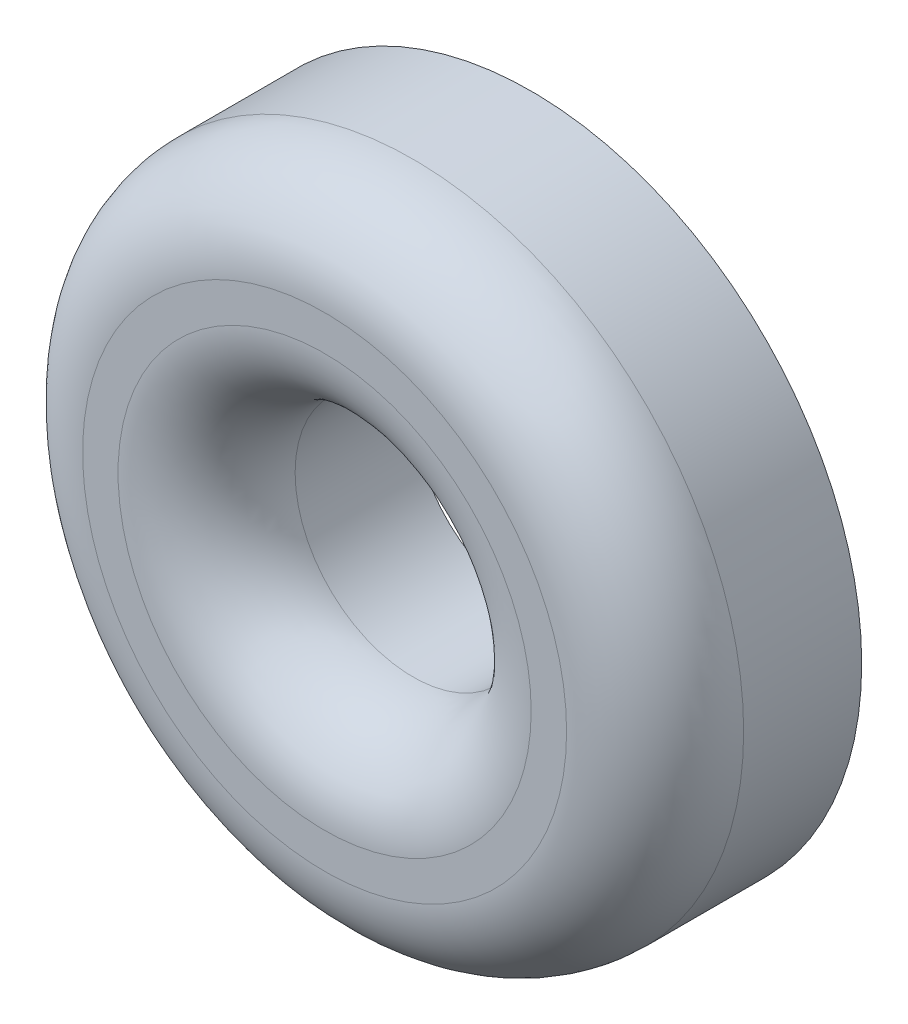
SolidWorks part; units mm, degrees
ref_plane "Front Plane" through (0, 0, 0) normal (0, 0, 1) x (1, 0, 0)
ref_plane "Top Plane" through (0, 0, 0) normal (0, 1, 0) x (1, 0, 0)
ref_plane "Right Plane" through (0, 0, 0) normal (1, 0, 0) x (0, 0, -1)
sketch "Sketch1" plane through (0, 0, 0) normal (0, 0, 1) x (1, 0, 0)
  circle A0 centre (0, 0) radius 2.8
  circle A1 centre (0, 0) radius 1
  dimension "D1" = 5.6
  dimension "D2" = 2
extrude "Boss-Extrude1" add sketch "Sketch1" along normal blind 1.75
fillet "Fillet1" radius 0.75 2 edges at (1, 0, 1.75) (2.8, 0, 1.75)
